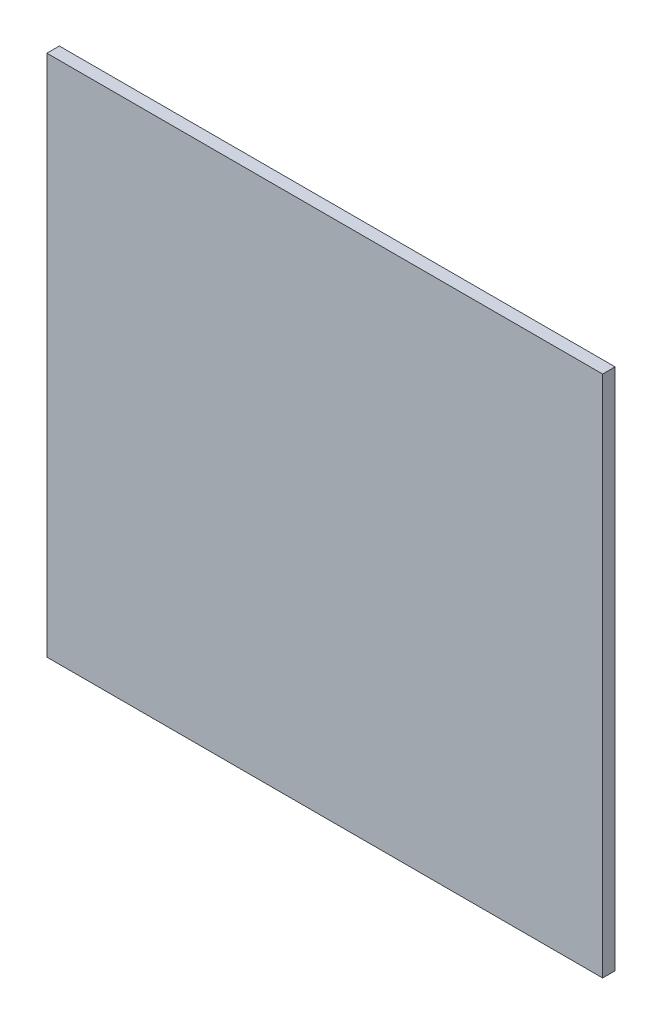
SolidWorks part; units mm, degrees
ref_plane "Plan de face" through (0, 0, 0) normal (0, 0, 1) x (1, 0, 0)
ref_plane "Plan de dessus" through (0, 0, 0) normal (0, 1, 0) x (1, 0, 0)
ref_plane "Plan de droite" through (0, 0, 0) normal (1, 0, 0) x (0, 0, -1)
sketch "Esquisse1" plane through (0, 0, 0) normal (0, 0, 1) x (1, 0, 0)
  line L1 (-29.1557, 20.1509) -> (820.8443, 20.1509)
  line L2 (-29.1557, 20.1509) -> (-29.1557, -779.8491)
  line L3 (-29.1557, -779.8491) -> (820.8443, -779.8491)
  line L4 (820.8443, 20.1509) -> (820.8443, -779.8491)
  dimension "D1" = 850
  dimension "D2" = 800
extrude "Boss.-Extru.1" add sketch "Esquisse1" along normal blind 19.05
